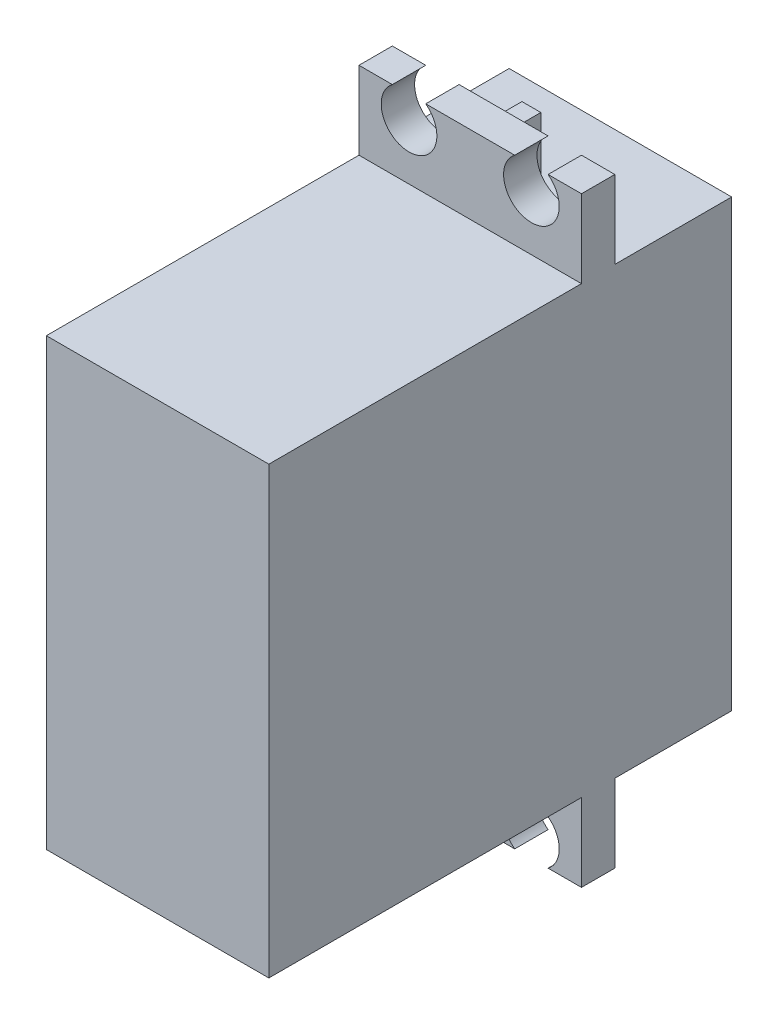
SolidWorks part; units mm, degrees
ref_plane "Front Plane" through (0, 0, 0) normal (0, 0, 1) x (1, 0, 0)
ref_plane "Top Plane" through (0, 0, 0) normal (0, 1, 0) x (1, 0, 0)
ref_plane "Right Plane" through (0, 0, 0) normal (1, 0, 0) x (0, 0, -1)
sketch "Sketch1" plane through (0, 0, 0) normal (0, 0, 1) x (1, 0, 0)
  line L1 (-10, -20) -> (10, -20)
  line L2 (-10, -20) -> (-10, 20)
  line L3 (-10, 20) -> (10, 20)
  line L4 (10, -20) -> (10, 20)
  line L5 (-10, -20) -> (10, 20) construction
  line L6 (-10, 20) -> (10, -20) construction
  point P0 (0, 0)
  dimension "D1" = 20
  dimension "D2" = 40
extrude "Boss-Extrude1" add sketch "Sketch1" along normal blind 41.6
sketch "Sketch2" plane through (0, 0, 0) normal (0, 0, -1) x (-1, 0, 0)
  line L0 (-10, 20) -> (10, 20) construction
  circle A0 centre (0, 10) radius 3
  circle A1 centre (0, 10) radius 1.5
  point P4 (0, 20)
  dimension "D1" = 6
  dimension "D3" = 3
  dimension "D2" = 10
extrude "Boss-Extrude2" add sketch "Sketch2" along normal blind 4
sketch "Sketch3" plane through (0, 0, 0) normal (0, 0, -1) x (-1, 0, 0)
  line L0 (-10, -20) -> (-10, 20) construction
  line L1 (-10, 0) -> (10, 0)
  line L2 (-10, -27) -> (-10, 27)
  line L3 (-10, 27) -> (10, 27)
  line L4 (10, -27) -> (10, 27)
  line L5 (10, 20) -> (10, -20) construction
  line L6 (-10, 20) -> (10, 20) construction
  line L7 (-10, -27) -> (10, -27)
  circle A0 centre (-5.5, 25) radius 2.5
  circle A1 centre (5.5, 25) radius 2.5
  circle A2 centre (5.5, -25) radius 2.5
  circle A3 centre (-5.5, -25) radius 2.5
  point P15 (-10, 0)
  line M6 (-10, -20) -> (10, -20)
  line M8 (10, 20) -> (-10, 20)
  dimension "D3" = 5
  dimension "D1" = 7
  dimension "D2" = 5
  dimension "D4" = 4.5
  dimension "D5" = 4.5
extrude "Boss-Extrude3" add sketch "Sketch3" along normal blind 3 from offset 13.5 contours A1 L3 A0 L2 L4 M8 | L7 A3 A2 L4 L2 M6 offset against normal yes
sketch "Sketch5" plane through (0, 0, 10.5) normal (0, 0, -1) x (-1, 0, 0)
  line L0 (10, 20) -> (-10, 20) construction
  line L1 (-0.85, 26) -> (0.85, 26)
  line L2 (-0.85, 26) -> (-0.85, 20)
  line L3 (-0.85, 20) -> (0.85, 20)
  line L4 (0.85, 26) -> (0.85, 20)
  line L5 (0.85, -20) -> (-0.85, -20)
  line L6 (0.85, -20) -> (0.85, -26)
  line L7 (0.85, -26) -> (-0.85, -26)
  line L8 (-0.85, -20) -> (-0.85, -26)
  line L9 (-10, -20) -> (10, -20) construction
  point P6 (0, 20)
  point P7 (0, 20)
  point P13 (0, -20)
  point P16 (0, -20)
  dimension "D1" = 6
  dimension "D2" = 1.7
  dimension "D3" = 6
  dimension "D4" = 1.7
extrude "Boss-Extrude4" add sketch "Sketch5" along normal blind 2.5
